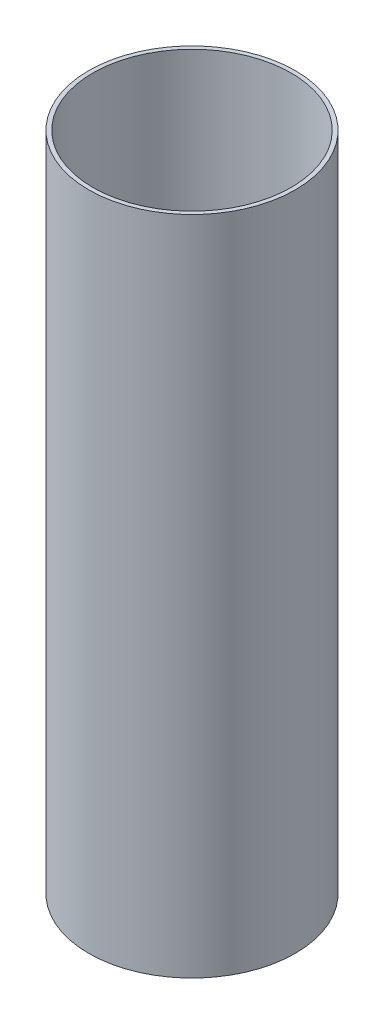
SolidWorks part; units mm, degrees
ref_plane "Front Plane" through (0, 0, 0) normal (0, 0, 1) x (1, 0, 0)
ref_plane "Top Plane" through (0, 0, 0) normal (0, 1, 0) x (1, 0, 0)
ref_plane "Right Plane" through (0, 0, 0) normal (1, 0, 0) x (0, 0, -1)
sketch "Sketch1" plane through (0, 0, 0) normal (0, 1, 0) x (1, 0, 0)
  circle A0 centre (0, 0) radius 38.1
  circle A1 centre (0, 0) radius 39.6748
  dimension "D1" = 76.2
  dimension "D2" = 79.3496
extrude "Boss-Extrude1" add sketch "Sketch1" along normal mid plane 254
equation "\"airframeInnerDiameter\"=3"
equation "\"outerDiameter\"=3.124"
equation "\"midAirframeLength\"=10"
equation "\"D1@Sketch1\"=\"airframeInnerDiameter\""
equation "\"D2@Sketch1\"=\"outerDiameter\""
equation "\"D1@Boss-Extrude1\"=\"midAirframeLength\""
